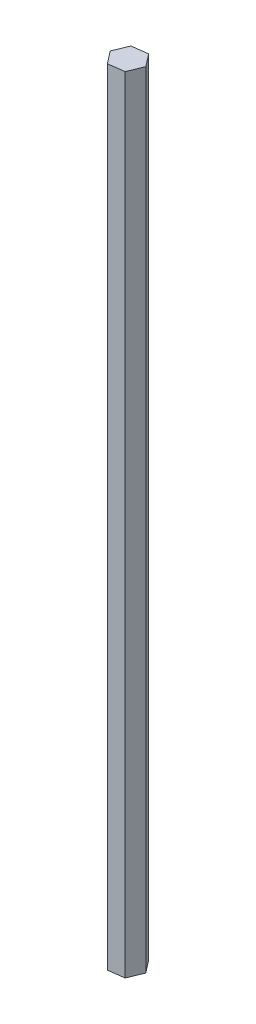
SolidWorks part; units mm, degrees
ref_plane "Front" through (0, 0, 0) normal (0, 0, 1) x (1, 0, 0)
ref_plane "Top" through (0, 0, 0) normal (0, 1, 0) x (1, 0, 0)
ref_plane "Right" through (0, 0, 0) normal (1, 0, 0) x (0, 0, -1)
sketch "Sketch1" plane through (0, 0, 0) normal (0, 1, 0) x (1, 0, 0)
  line L1 (3.3601, -4.3534) -> (5.4502, 0.7332)
  line L2 (5.4502, 0.7332) -> (2.0901, 5.0866)
  line L3 (2.0901, 5.0866) -> (-3.3601, 4.3534)
  line L4 (-3.3601, 4.3534) -> (-5.4502, -0.7332)
  line L5 (-5.4502, -0.7332) -> (-2.0901, -5.0866)
  line L6 (-2.0901, -5.0866) -> (3.3601, -4.3534)
  circle A0 centre (0, 0) radius 4.7625 construction
  dimension "D1" = 9.525
extrude "Boss-Extrude1" add sketch "Sketch1" along normal mid plane 273.05
